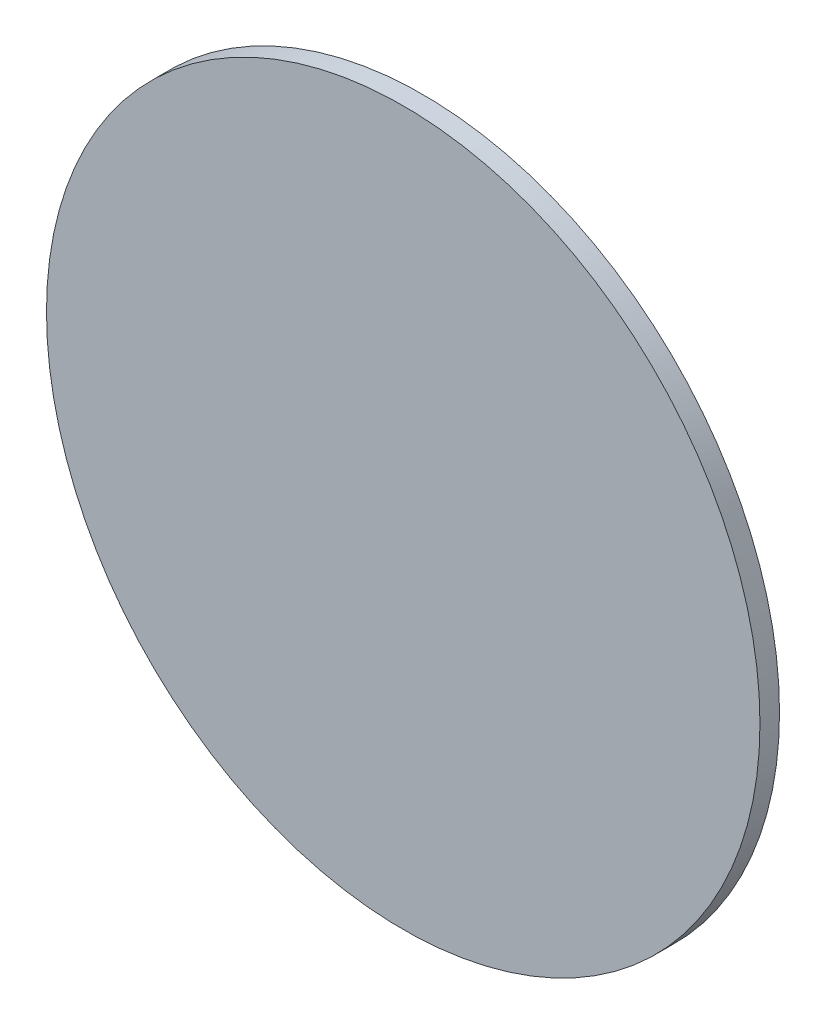
SolidWorks part; units mm, degrees
ref_plane "Front Plane" through (0, 0, 0) normal (0, 0, 1) x (1, 0, 0)
ref_plane "Top Plane" through (0, 0, 0) normal (0, 1, 0) x (1, 0, 0)
ref_plane "Right Plane" through (0, 0, 0) normal (1, 0, 0) x (0, 0, -1)
sketch "Sketch1" plane through (0, 0, 0) normal (0, 0, 1) x (1, 0, 0)
  circle A0 centre (0, 0) radius 36.5
  dimension "D1" = 73
extrude "Boss-Extrude1" add sketch "Sketch1" along normal blind 2
